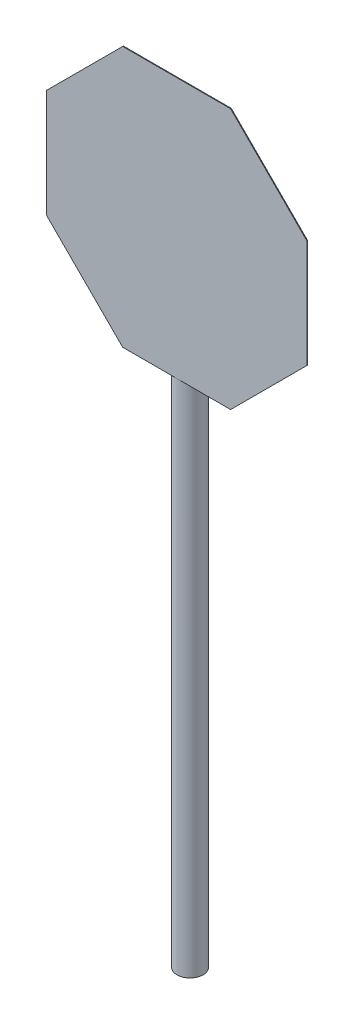
SolidWorks part; units mm, degrees
ref_plane "Front Plane" through (0, 0, 0) normal (0, 0, 1) x (1, 0, 0)
ref_plane "Top Plane" through (0, 0, 0) normal (0, 1, 0) x (1, 0, 0)
ref_plane "Right Plane" through (0, 0, 0) normal (1, 0, 0) x (0, 0, -1)
sketch "Sketch3" plane through (0, 0, 0) normal (0, 1, 0) x (1, 0, 0)
  circle A0 centre (0, 0) radius 38.1
  dimension "D1" = 76.2
extrude "Boss-Extrude1" add sketch "Sketch3" along normal blind 2133.6
sketch "Sketch5" plane through (0, 0, 0) normal (0, 0, 1) x (1, 0, 0)
  line L1 (-381, 1734.4846) -> (-157.8154, 1511.3)
  line L2 (-157.8154, 1511.3) -> (157.8154, 1511.3)
  line L3 (157.8154, 1511.3) -> (381, 1734.4846)
  line L4 (381, 1734.4846) -> (381, 2050.1154)
  line L5 (381, 2050.1154) -> (157.8154, 2273.3)
  line L6 (157.8154, 2273.3) -> (-157.8154, 2273.3)
  line L7 (-157.8154, 2273.3) -> (-381, 2050.1154)
  line L8 (-381, 2050.1154) -> (-381, 1734.4846)
  circle A0 centre (0, 1892.3) radius 381 construction
  point P1 (0, 0)
  dimension "D1" = 762
  dimension "D2" = 2273.3
extrude "Boss-Extrude2" add sketch "Sketch5" along normal mid plane 2.032 from offset 38.1
